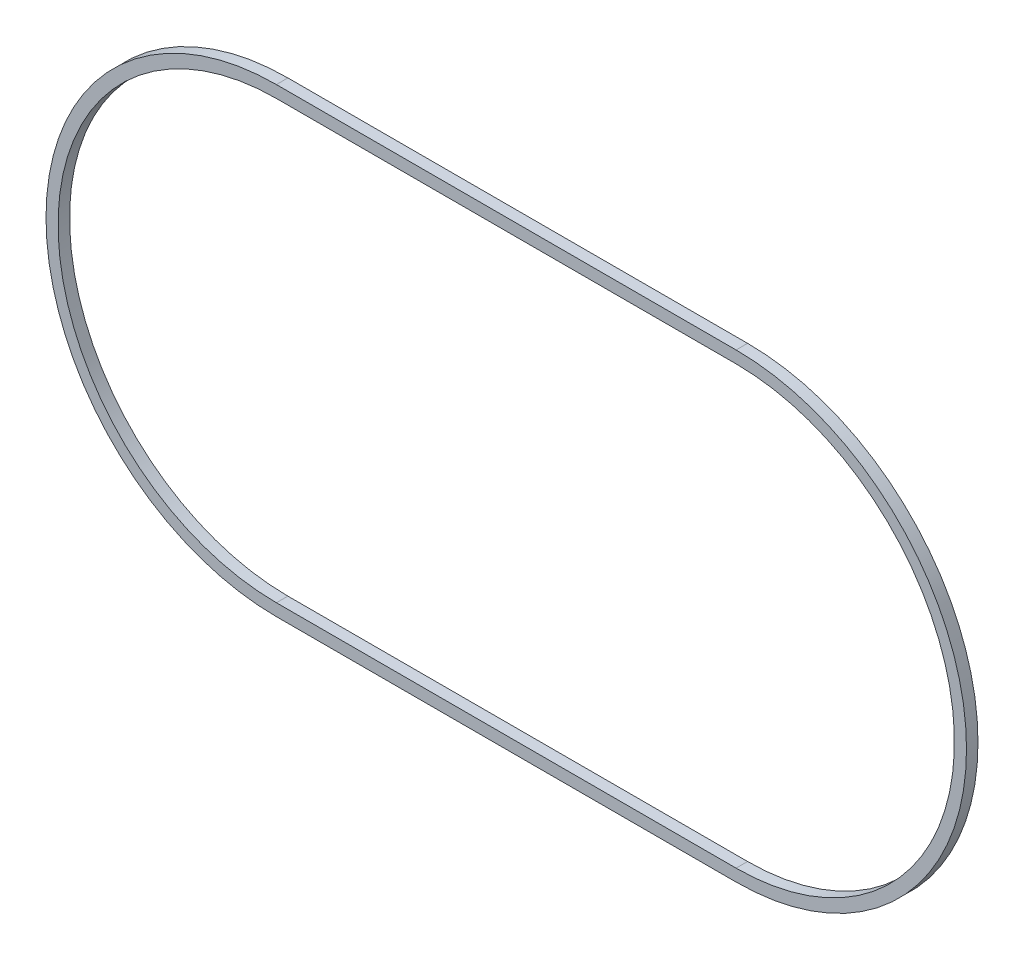
SolidWorks part; units mm, degrees
material "Латунь"
ref_plane "Спереди" through (0, 0, 0) normal (0, 0, 1) x (1, 0, 0)
ref_plane "Сверху" through (0, 0, 0) normal (0, 1, 0) x (1, 0, 0)
ref_plane "Справа" through (0, 0, 0) normal (1, 0, 0) x (0, 0, -1)
other "Configuration Table"
sketch "Эскиз1" plane through (0, 0, 0) normal (0, 0, 1) x (1, 0, 0)
  line L0 (-40, 0) -> (40, 0) construction
  line L1 (-40, 38) -> (40, 38)
  line L2 (-40, 40) -> (40, 40) construction
  line L3 (-40, -40) -> (40, -40) construction
  line L4 (-40, -38) -> (40, -38)
  line L5 (-40, -40.1) -> (40, -40.1)
  line L6 (-40, 40.1) -> (40, 40.1)
  arc A0 (-40, 40) -> (-40, -40) centre (-40, 0) ccw construction
  arc A1 (40, -40) -> (40, 40) centre (40, 0) ccw construction
  arc A2 (40, -38) -> (40, 38) centre (40, 0) ccw
  arc A3 (-40, 38) -> (-40, -38) centre (-40, 0) ccw
  arc A4 (-40, 40.1) -> (-40, -40.1) centre (-40, 0) ccw
  arc A5 (40, -40.1) -> (40, 40.1) centre (40, 0) ccw
  point P5 (0, 0)
  dimension "D1" = 80
  dimension "D2" = 160
  dimension "D3" = 2
  dimension "D4" = 2.1
extrude "Бобышка-Вытянуть1" add sketch "Эскиз1" along normal blind 2
